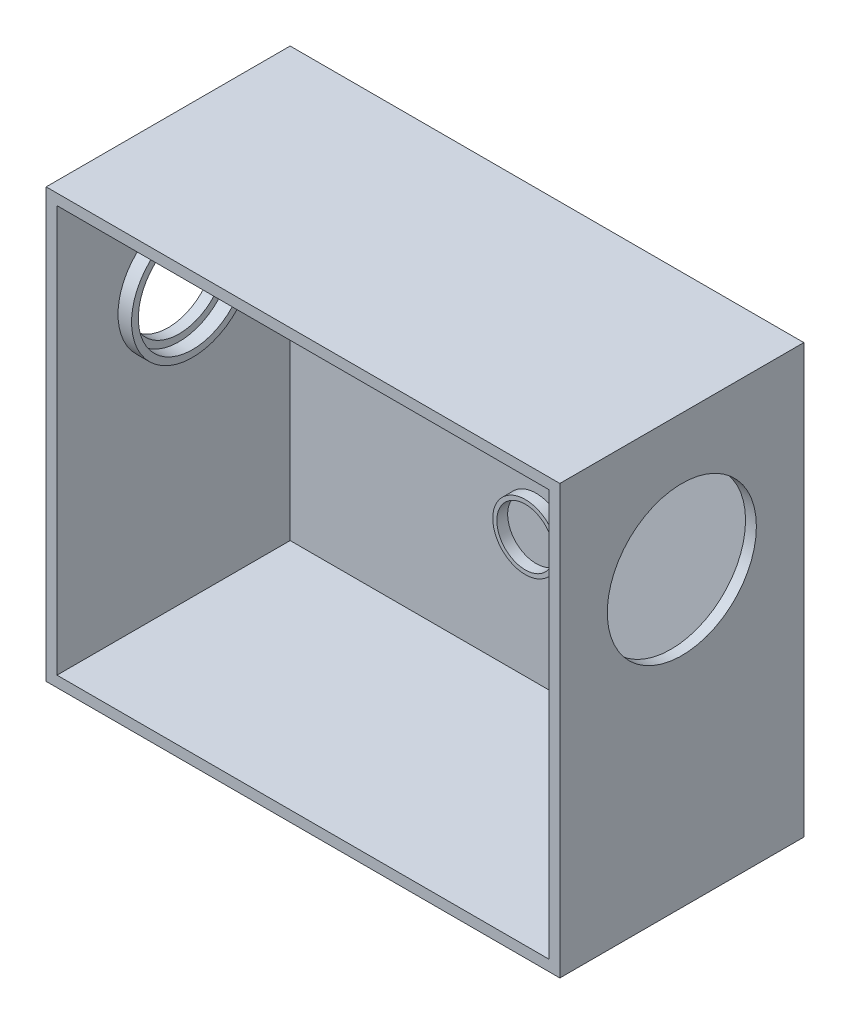
SolidWorks part; units mm, degrees
ref_plane "Alzado" through (0, 0, 0) normal (0, 0, 1) x (1, 0, 0)
ref_plane "Planta" through (0, 0, 0) normal (0, 1, 0) x (1, 0, 0)
ref_plane "Vista lateral" through (0, 0, 0) normal (1, 0, 0) x (0, 0, -1)
sketch "Croquis1" plane through (0, 0, 0) normal (0, 0, 1) x (1, 0, 0)
  line L0 (-189.5, 158) -> (189.5, 158)
  line L1 (-181.5, -150) -> (181.5, -150) construction
  line L2 (-181.5, -150) -> (-181.5, 150) construction
  line L3 (-181.5, 150) -> (181.5, 150) construction
  line L4 (181.5, -150) -> (181.5, 150) construction
  line L5 (-181.5, -150) -> (181.5, 150) construction
  line L6 (-181.5, 150) -> (181.5, -150) construction
  line L7 (189.5, -158) -> (189.5, 158)
  line L8 (-189.5, -158) -> (189.5, -158)
  line L9 (-189.5, -158) -> (-189.5, 158)
  point P0 (0, 0)
  dimension "D1" = 363
  dimension "D2" = 300
  dimension "D3" = 8
extrude "Saliente-Extruir1" add sketch "Croquis1" along normal blind 180
shell "Vaciado1" thickness 8
sketch "Croquis2" plane through (-189.5, 0, 0) normal (-1, 0, 0) x (0, 0, 1)
  line L0 (0, 158) -> (90, 158) construction
  line L1 (180, 158) -> (0, 158) construction
  circle A0 centre (90, 58) radius 35
extrude "Cortar-Extruir4" cut sketch "Croquis2" against normal blind 20 contours A0
sketch "Croquis4" plane through (-181.5, 0, 0) normal (1, 0, 0) x (0, 0, -1)
  circle A1 centre (-90, 58) radius 40
  circle A2 centre (-90, 58) radius 45
extrude "Saliente-Extruir4" add sketch "Croquis4" along normal blind 10
sketch "Croquis6" plane through (189.5, 0, 0) normal (1, 0, 0) x (0, 0, -1)
  line L0 (-90, 158) -> (-90, 58) construction
  line L1 (-180, 158) -> (0, 158) construction
  circle A0 centre (-90, 58) radius 55
extrude "Cortar-Extruir6" cut sketch "Croquis6" against normal blind 10 contours A0
sketch "Croquis7" plane through (0, 0, 8) normal (0, 0, 1) x (1, 0, 0)
  line L0 (0, 150) -> (0, -53) construction
  line L1 (181.5, 150) -> (-181.5, 150) construction
  circle A0 centre (0, -53) radius 24
  circle A2 centre (0, -53) radius 21
  dimension "D1" = 42
extrude "Saliente-Extruir9" add sketch "Croquis7" along normal blind 8
